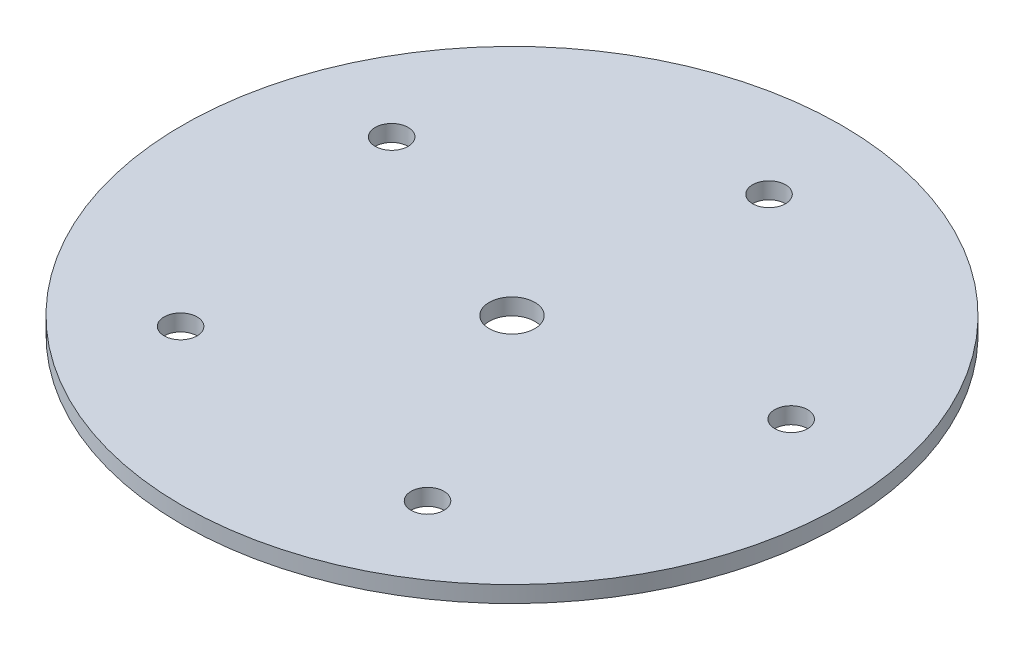
SolidWorks part; units mm, degrees
ref_plane "Front Plane" through (0, 0, 0) normal (0, 0, 1) x (1, 0, 0)
ref_plane "Top Plane" through (0, 0, 0) normal (0, 1, 0) x (1, 0, 0)
ref_plane "Right Plane" through (0, 0, 0) normal (1, 0, 0) x (0, 0, -1)
sketch "Sketch1" plane through (0, 0, 0) normal (0, 1, 0) x (1, 0, 0)
  circle A0 centre (0, 0) radius 60
extrude "Boss-Extrude1" add sketch "Sketch1" along normal blind 3
sketch "Sketch2" plane through (0, 3, 0) normal (0, 1, 0) x (1, 0, 0)
  circle A0 centre (0, 0) radius 4.15
extrude "Cut-Extrude1" cut sketch "Sketch2" against normal blind 5
sketch "Sketch3" plane through (0, 3, 0) normal (0, 1, 0) x (1, 0, 0)
  circle A0 centre (-28.4516, -31.8833) radius 3
  circle A1 centre (-39.1148, 17.2066) radius 3
  circle A2 centre (4.2773, 42.5176) radius 3
  circle A3 centre (41.7584, 9.0707) radius 3
  circle A4 centre (21.5308, -36.9116) radius 3
  point P12 (0, 0)
  dimension "D1" = 5
extrude "Cut-Extrude2" cut sketch "Sketch3" against normal blind 10
